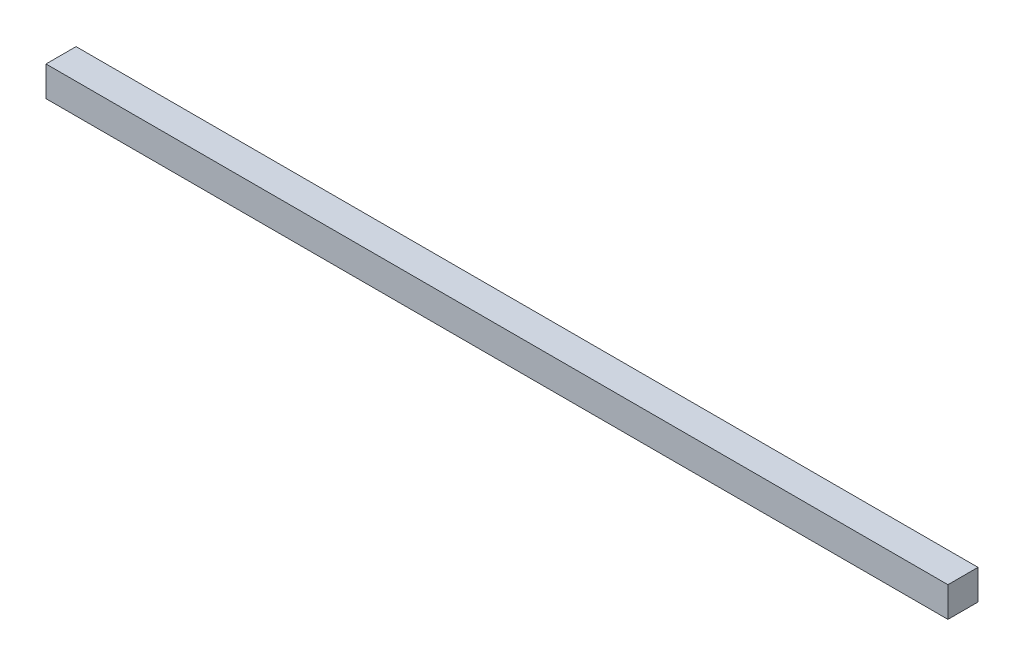
SolidWorks part; units mm, degrees
ref_plane "Alzado" through (0, 0, 0) normal (0, 0, 1) x (1, 0, 0)
ref_plane "Planta" through (0, 0, 0) normal (0, 1, 0) x (1, 0, 0)
ref_plane "Vista lateral" through (0, 0, 0) normal (1, 0, 0) x (0, 0, -1)
sketch "Croquis1" plane through (0, 0, 0) normal (0, 0, 1) x (1, 0, 0)
  line L1 (-101.785, 19.6712) -> (-11.785, 19.6712)
  line L2 (-101.785, 19.6712) -> (-101.785, 16.6712)
  line L3 (-101.785, 16.6712) -> (-11.785, 16.6712)
  line L4 (-11.785, 19.6712) -> (-11.785, 16.6712)
  dimension "D1" = 90
  dimension "D2" = 3
extrude "Saliente-Extruir1" add sketch "Croquis1" along normal blind 3
